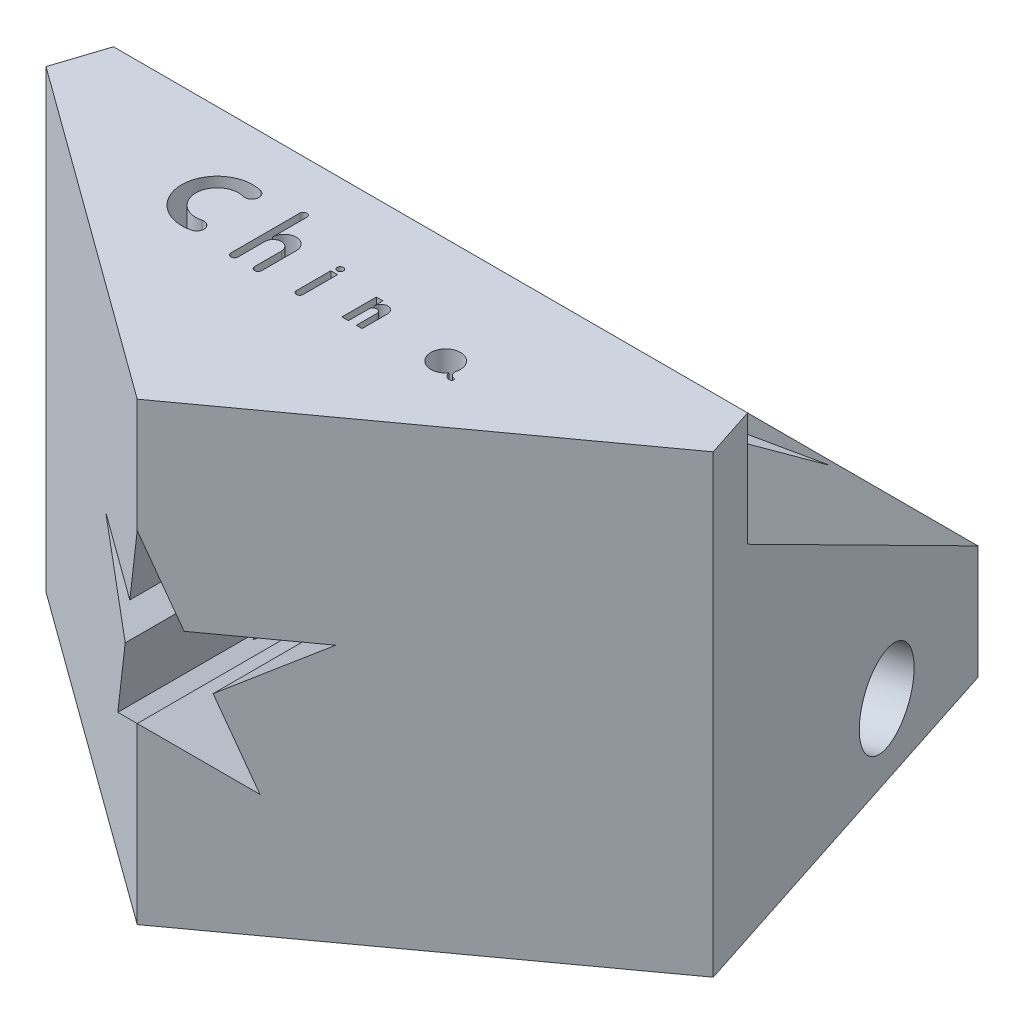
SolidWorks part; units mm, degrees
ref_plane "前视基准面" through (0, 0, 0) normal (0, 0, 1) x (1, 0, 0)
ref_plane "上视基准面" through (0, 0, 0) normal (0, 1, 0) x (1, 0, 0)
ref_plane "右视基准面" through (0, 0, 0) normal (1, 0, 0) x (0, 0, -1)
other "Configuration Table"
sketch "草图1" plane through (0, 0, 0) normal (0, 1, 0) x (1, 0, 0)
  line L0 (-14.5, 30) -> (14.5, 30)
  line L1 (-14.5, 30) -> (-23.4615, 2.4194)
  line L2 (-23.4615, 2.4194) -> (0, -14.6264)
  line L3 (0, -14.6264) -> (23.4615, 2.4194)
  line L4 (23.4615, 2.4194) -> (14.5, 30)
  dimension "D1" = 29
  dimension "D2" = 29
  dimension "D3" = 29
  dimension "D4" = 29
  dimension "D5" = 29
  dimension "D6" = 108
  dimension "D7" = 108
extrude "凸台-拉伸1" add sketch "草图1" along normal mid plane 32
sketch "草图3" plane through (0, 0, 0) normal (1, 0, 0) x (0, 0, -1)
  line L0 (6, 16) -> (6, 8)
  line L1 (-14.6264, 16) -> (2.4194, 16) construction
  line L2 (6, 8) -> (30, -8)
  line L3 (30, 16) -> (30, -16) construction
  line L4 (30, -8) -> (30, 16)
  line L5 (2.4194, 16) -> (30, 16) construction
  line L6 (30, 16) -> (6, 16)
  dimension "D1" = 8
  dimension "D2" = 24
  dimension "D3" = 24
extrude "切除-拉伸1" cut sketch "草图3" against normal through all both and the other way through all
sketch "草图4" plane through (21.9322, 0, -7.1262) normal (0.9511, 0, -0.309) x (-0.309, 0, -0.9511)
  line L0 (24.0509, -8) -> (24.0509, -16) construction
  line L2 (-4.9491, -16) -> (24.0509, -16) construction
  circle A0 centre (14.0509, -11) radius 3
  dimension "D1" = 6
  dimension "D2" = 10
  dimension "D3" = 5
extrude "切除-拉伸2" cut sketch "草图4" against normal blind 23
mirror "镜向1" about plane through (0, 0, 0) normal (1, 0, 0) of "切除-拉伸2"
sketch "草图7" plane through (0, 0, 0) normal (0, 0, 1) x (1, 0, 0)
  line L1 (0, 16) -> (0, -16) construction
  line L7 (0, 8) -> (-1.9098, 2.1221)
  line L8 (-5, -7.3884) -> (0, -3.7557)
  line L9 (8.0902, 2.1221) -> (1.9098, 2.1221)
  line L10 (-8.0902, 2.1221) -> (-3.0902, -1.5106)
  line L11 (5, -7.3884) -> (3.0902, -1.5106)
  line L12 (0, -3.7557) -> (5, -7.3884)
  line L13 (3.0902, -1.5106) -> (8.0902, 2.1221)
  line L14 (1.9098, 2.1221) -> (0, 8)
  line L15 (-1.9098, 2.1221) -> (-8.0902, 2.1221)
  line L16 (-3.0902, -1.5106) -> (-5, -7.3884)
  dimension "D1" = 8
  dimension "D2" = 6.1803
  dimension "D3" = 5.8779
  dimension "D5" = 10
  dimension "D6" = 10
  dimension "D7" = 10
extrude "切除-拉伸3" cut sketch "草图7" against normal through all both and the other way through all
sketch "草图8" plane through (0, 16, 0) normal (0, 1, 0) x (1, 0, 0)
  line L0 (-5.1138, 2.4206) -> (-5.1138, 0)
  line L1 (-3.4482, 0) -> (-3.4482, -2.4206)
  line L2 (-5.6138, 2.4206) -> (-5.6138, -2.4206)
  line L3 (-3.9482, -0.5369) -> (-3.9482, -2.4206)
  line L4 (-5.1138, -0.5369) -> (-5.1138, -2.4206)
  line L5 (-1.0134, 0) -> (-1.0134, -2.4206)
  line L6 (-0.5385, 0) -> (-0.5385, -2.4206)
  line L7 (-1.0134, 0) -> (-0.5385, 0)
  line L8 (2.1878, 0) -> (2.1878, -2.4206)
  line L9 (2.1878, -2.4206) -> (2.6485, -2.4206)
  line L10 (2.6485, -2.4206) -> (2.6485, -0.9848)
  line L11 (2.6485, 0) -> (2.1878, 0)
  line L12 (3.2055, -2.4206) -> (3.611, -2.4206)
  line L13 (3.2055, -2.4206) -> (3.2055, -0.9848)
  line L14 (3.611, -2.4206) -> (3.611, -0.6226)
  line L15 (2.6485, -0.6226) -> (2.6485, 0)
  arc A0 (-8.375, 2.4206) -> (-8.375, -2.4206) centre (-9, 0) ccw
  arc A1 (-8.625, 1.4524) -> (-8.625, -1.4524) centre (-9, 0) ccw
  arc A2 (-8.625, 1.4524) -> (-8.375, 2.4206) centre (-8.5, 1.9365) ccw
  arc A3 (-8.375, -2.4206) -> (-8.625, -1.4524) centre (-8.5, -1.9365) ccw
  arc A5 (-3.9482, -0.5369) -> (-5.1138, -0.5369) centre (-4.531, -0.5369) ccw
  arc A6 (-5.1138, 2.4206) -> (-5.6138, 2.4206) centre (-5.3638, 2.4206) ccw
  arc A7 (-5.6138, -2.4206) -> (-5.1138, -2.4206) centre (-5.3638, -2.4206) ccw
  arc A8 (-3.9482, -2.4206) -> (-3.4482, -2.4206) centre (-3.6982, -2.4206) ccw
  arc A9 (-3.4482, 0) -> (-5.1138, 0) centre (-4.281, 0) ccw
  arc A10 (-1.0134, -2.4206) -> (-0.5385, -2.4206) centre (-0.7759, -2.4206) ccw
  circle A11 centre (-0.7759, 0.4314) radius 0.2193
  arc A12 (2.6485, -0.9848) -> (3.2055, -0.9848) centre (2.927, -0.9848) cw
  arc A13 (2.6485, -0.6226) -> (3.611, -0.6226) centre (3.1297, -0.6226) cw
  arc A15 (9.5125, -1.7534) -> (9.365, -2.0545) centre (8.5174, -1.4524) ccw
  arc A16 (9.5125, -1.7534) -> (9.9239, -2.2339) centre (9.9584, -1.788) ccw
  arc A17 (9.365, -2.0545) -> (9.8207, -2.4659) centre (9.7986, -2.0323) ccw
  arc A18 (9.8207, -2.4659) -> (9.9239, -2.2339) centre (9.8135, -2.3238) ccw
  dimension "D1" = 5
  dimension "D2" = 3
  dimension "D3" = 8.5
  dimension "D4" = 9
  dimension "D5" = 8.5
  dimension "D6" = 0.5
  dimension "D7" = 0.5
extrude "切除-拉伸4" cut sketch "草图8" against normal through all
